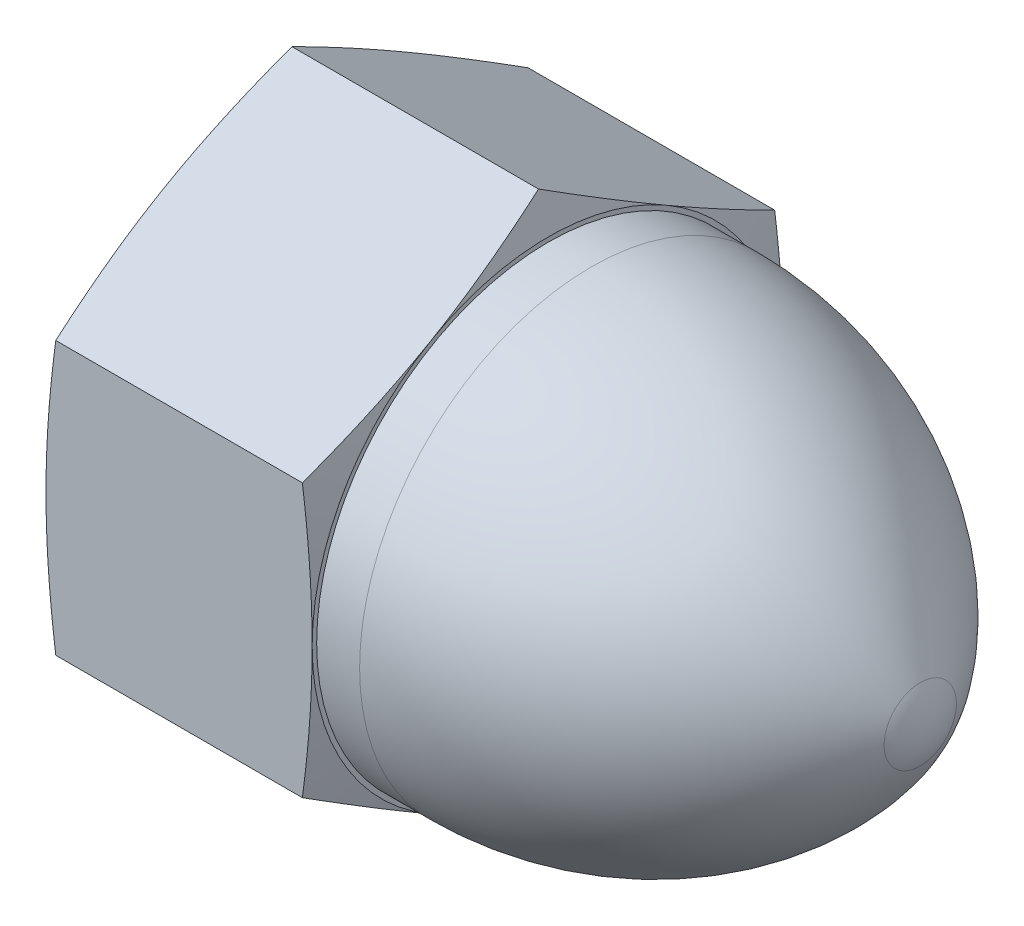
SolidWorks part; units mm, degrees
extrude "BaseNut" add sketch "BaseNutSke" along normal blind 20.574
sketch "BaseNutSke" plane through (0, 0, 0) normal (1, 0, 0) x (0, 0, -1)
  line L6 (18.2562, 10.5403) -> (18.2562, -10.5403)
  line L7 (-18.2562, 10.5403) -> (-18.2563, -10.5403)
  line L8 (18.2562, 10.5403) -> (0, 21.0805)
  line L9 (0, 21.0805) -> (-18.2562, 10.5403)
  line L10 (-18.2563, -10.5403) -> (0, -21.0805)
  line L11 (0, -21.0805) -> (18.2562, -10.5403)
  dimension "Width_flats" = 36.5125
  dimension "D1" = 120
  dimension "D2" = 18.2562
  dimension "D3" = 18.2562
  dimension "D4" = 60
revolve "DoubleChamfer" cut sketch "Sketch4" angle 360 about L10
sketch "Sketch4" plane through (0, 0, 0) normal (0, 0, 1) x (1, 0, 0)
  line L0 (0, 18.2562) -> (1.9499, 25.5333)
  line L1 (20.574, 18.2562) -> (18.6245, 25.5333)
  line L2 (1.9499, 25.5333) -> (18.6245, 25.5333)
  line L3 (20.574, 18.2562) -> (33.274, 18.2562)
  line L4 (33.274, 18.2562) -> (33.274, 43.6562)
  line L5 (33.274, 43.6562) -> (-12.7, 43.6562)
  line L6 (0, 18.2562) -> (-12.7, 18.2562)
  line L7 (-12.7, 18.2562) -> (-12.7, 43.6562)
  line L8 (20.574, 21.0805) -> (20.574, 10.5403) construction
  line L9 (0, 21.0805) -> (0, 10.5403) construction
  line L10 (0, 0) -> (57.15, 0) construction
  point P17 (20.574, 18.2562)
  dimension "D1" = 14.997
  dimension "D2" = 15
  dimension "D3" = 12.7
  dimension "D4" = 12.7
  dimension "D5" = 18.1229
  dimension "D6" = 25.4
  dimension "D7" = 18.2562
ref_plane "Plane1" through (0, 0, 0) normal (0, 0, 1) x (1, 0, 0)
ref_plane "Plane2" through (0, 0, 0) normal (0, 1, 0) x (1, 0, 0)
ref_plane "Plane3" through (0, 0, 0) normal (1, 0, 0) x (0, 0, -1)
sketch "Sketch3" plane through (0, 0, 0) normal (0, 0, 1) x (1, 0, 0)
  line L0 (0, 0) -> (63.5, 0) construction
  line L1 (0, 10.5403) -> (0, -10.5403) construction
  line L2 (50.038, 0) -> (0, 0)
  line L3 (0, 17.907) -> (23.8939, 17.907)
  line L4 (0, -17.907) -> (22.225, -17.907) construction
  line L5 (0, 17.907) -> (0, 0)
  arc A0 (50.038, 0) -> (49.3273, 2.7926) centre (44.196, 0) ccw
  arc A1 (49.3273, 2.7926) -> (23.8939, 17.907) centre (23.8939, -11.049) ccw
  dimension "Nose_radius" = 5.842
  dimension "Body_radius" = 28.956
  dimension "Overall_ht" = 50.038
  dimension "Body_dia" = 35.814
revolve "Crown" add sketch "Sketch3" angle 360 about L0
sketch "Sketch5" plane through (0, 0, 0) normal (0, 0, 1) x (1, 0, 0)
  line L0 (0, 0) -> (44.45, 0) construction
  line L1 (0, 11.1125) -> (35.052, 11.1125)
  line L2 (0, 15.8104) -> (0, 0) construction
  line L3 (35.052, 11.1125) -> (41.7291, 0)
  line L4 (0, 0) -> (63.5, 0) construction
  line L5 (41.7291, 0) -> (0, 0)
  line L6 (0, 0) -> (0, 11.1125)
  line L7 (35.052, -11.1125) -> (41.7291, 0) construction
  line L8 (0, -11.1125) -> (35.052, -11.1125) construction
revolve "TapDrill" cut sketch "Sketch5"
cosmetic thread "ThreadCosmetic" [suppressed]
revolve "EndChamfer" cut sketch "EndChamferSketch" angle 360 about L4
sketch "EndChamferSketch" plane through (0, 0, 0) normal (0, 0, 1) x (1, 0, 0)
  line L0 (-0.0254, 12.7) -> (0.0254, 12.7)
  line L1 (0.0254, 12.7) -> (1.2481, 10.9537)
  line L2 (1.2481, 10.9537) -> (-0.0254, 10.9537)
  line L3 (-0.0254, 10.9537) -> (-0.0254, 12.7)
  line L4 (-3.175, 0) -> (-15.875, 0) construction
  dimension "D1" = 0.0508
  dimension "D2" = 35
  dimension "ChamferDepth" = 1.7463
  dimension "ThreadMajor" = 12.7
  dimension "D3" = 0.0254
sketch "ThdSchSke" plane through (0, 0, 0) normal (0, 1, 0) x (1, 0, 0)
  line L0 (0.0381, 12.7) -> (-1.0735, 11.1125)
  line L1 (-1.0735, 11.1125) -> (-1.0735, 4.2333)
  line L2 (-1.0735, 4.2333) -> (1.1497, 4.2333)
  line L3 (1.1497, 4.2333) -> (1.1497, 11.1125)
  line L4 (1.1497, 11.1125) -> (0.0381, 12.7)
  line L5 (-25.4, 0) -> (1.1497, 0) construction
  line L9 (3.2131, 3.175) -> (3.2131, -3.175) construction
  dimension "Tap_drill" = 22.225
  dimension "OverCut" = 8.4667
  dimension "Thread_major" = 25.4
  dimension "D1" = 0.0381
revolve "ThreadSchematic" [suppressed] cut sketch "ThdSchSke" angle 360 about L5
pattern_linear "ThdSchPat" [suppressed]
equation "\"D2@BaseNutSke\" = \"Width_flats@BaseNutSke\" / 2"
equation "\"D3@BaseNutSke\" = \"Width_flats@BaseNutSke\" / 2"
equation "\"D7@Sketch4\" = \"Width_flats@BaseNutSke\" / 2"
equation "\"Thread_major@ThdSchSke\" = \"Thread_nominal@ThreadCosmetic\""
equation "\"Tap_drill@ThdSchSke\" = \"Thread_min@Sketch5\""
equation "\"OverCut@ThdSchSke\" =  \"Thread_nominal@ThreadCosmetic\" / 3"
equation "\"Num_threads@ThdSchPat\" = int(  ( \"Hex_ht@BaseNut\" - 0.002 ) / \"Advance@ThdSchSke\" + 0.999 )  + 1"
equation "\"Advance@ThdSchPat\" = ( \"Hex_ht@BaseNut\" - 0.002 ) /  (\"Num_threads@ThdSchPat\" - 1) 'relax it"
equation "' \"Num_threads@ThdSchPat\" = \"Num_threads@ThdSchPat\" - sgn( \"Num_threads@ThdSchPat\" - 1) '---chamfered tips only---"
equation "\"ThreadMajor@EndChamferSketch\" = \"Thread_nominal@ThreadCosmetic\" * 0.5"
equation "\"ChamferDepth@EndChamferSketch\" = (\"Thread_nominal@ThreadCosmetic\" - \"Thread_min@Sketch5\") * 0.55"
